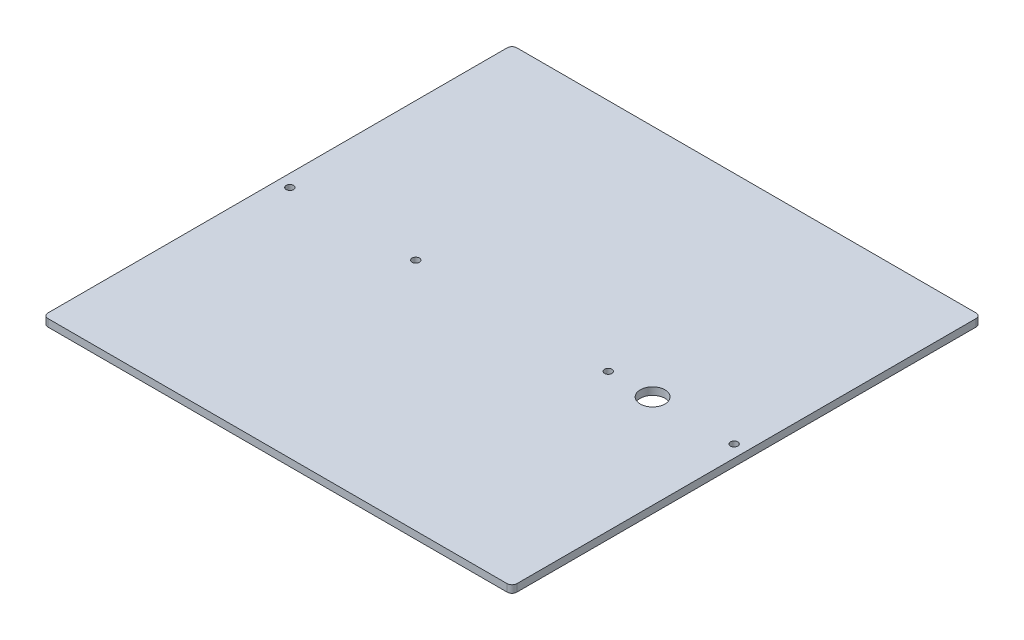
SolidWorks part; units mm, degrees
ref_plane "Front Plane" through (0, 0, 0) normal (0, 0, 1) x (1, 0, 0)
ref_plane "Top Plane" through (0, 0, 0) normal (0, 1, 0) x (1, 0, 0)
ref_plane "Right Plane" through (0, 0, 0) normal (1, 0, 0) x (0, 0, -1)
sketch "Sketch1" plane through (0, 0, 0) normal (0, 1, 0) x (1, 0, 0)
  line L0 (0, 0) -> (190, 0)
  line L1 (190, 0) -> (190, 190)
  line L2 (190, 190) -> (0, 190)
  line L3 (0, 190) -> (0, 0)
  line L4 (190, 95) -> (0, 95) construction
  line L5 (190, 95) -> (185, 95)
  line L6 (0, 95) -> (5, 95)
  line L7 (95, 121) -> (95, 69) construction
  line L8 (56, 95) -> (56, 121) construction
  line L9 (56, 121) -> (134, 121) construction
  line L10 (134, 121) -> (134, 69) construction
  line L11 (134, 69) -> (56, 69) construction
  line L12 (56, 69) -> (56, 95) construction
  line L13 (56, 95) -> (134, 95) construction
  circle A0 centre (185, 95) radius 1.5
  circle A1 centre (5, 95) radius 1.5
  circle A2 centre (134, 95) radius 1.5
  circle A3 centre (56, 95) radius 1.5
  circle A5 centre (151.9701, 95) radius 5
  dimension "D1" = 190
  dimension "D2" = 190
extrude "Boss-Extrude1" add sketch "Sketch1" along normal blind 3
fillet "Fillet1" radius 2 4 edges at (0, 1.5, -190) (190, 1.5, -190) (190, 1.5, 0) (0, 1.5, 0)
